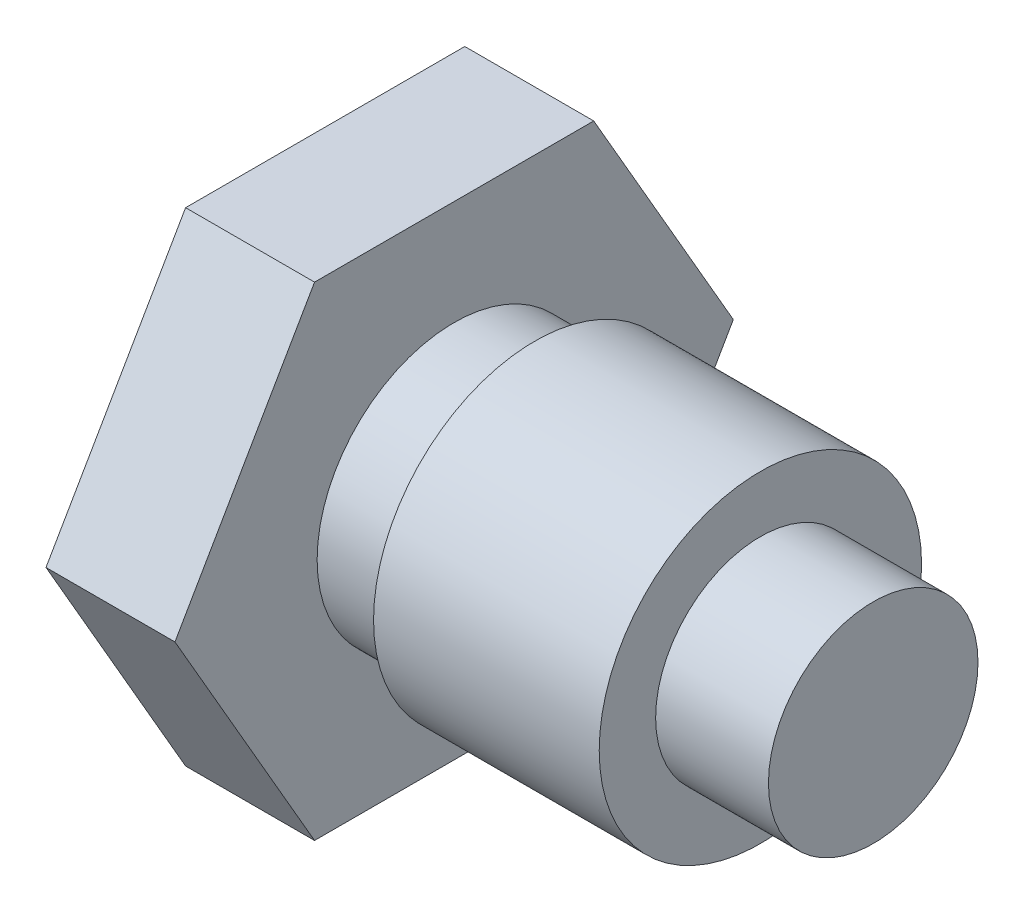
SolidWorks part; units mm, degrees
ref_plane "前视基准面" through (0, 0, 0) normal (0, 0, 1) x (1, 0, 0)
ref_plane "上视基准面" through (0, 0, 0) normal (0, 1, 0) x (1, 0, 0)
ref_plane "右视基准面" through (0, 0, 0) normal (1, 0, 0) x (0, 0, -1)
other "Configuration Table"
ref_plane "P_01_HEX_AF30" through (0, 0, 0) normal (1, 0, 0) x (0, 0, -1)
sketch "草图1" plane through (0, 0, 0) normal (1, 0, 0) x (0, 0, -1)
  line L1 (17.3205, 0) -> (8.6602, 15)
  line L2 (8.6602, 15) -> (-8.6603, 15)
  line L3 (-8.6603, 15) -> (-17.3205, 0)
  line L4 (-17.3205, 0) -> (-8.6602, -15)
  line L5 (-8.6602, -15) -> (8.6603, -15)
  line L6 (8.6603, -15) -> (17.3205, 0)
  circle A0 centre (0, 0) radius 15 construction
extrude "01_HEX_AF30" add sketch "草图1" along normal blind 8
sketch "草图2" plane through (0, 0, 0) normal (0, 0, 1) x (1, 0, 0)
  line L0 (3, 0) -> (39, 0) construction
  line L1 (8, 0) -> (8, 8.5)
  line L2 (8, 8.5) -> (13, 8.5)
  line L3 (13, 8.5) -> (13, 10)
  line L4 (13, 10) -> (27, 10)
  line L5 (27, 10) -> (27, 6.5)
  line L6 (27, 6.5) -> (34, 6.5)
  line L7 (34, 6.5) -> (34, 0)
  line L8 (34, 0) -> (8, 0)
revolve "02_BODY" add sketch "草图2" angle 360 about L0
